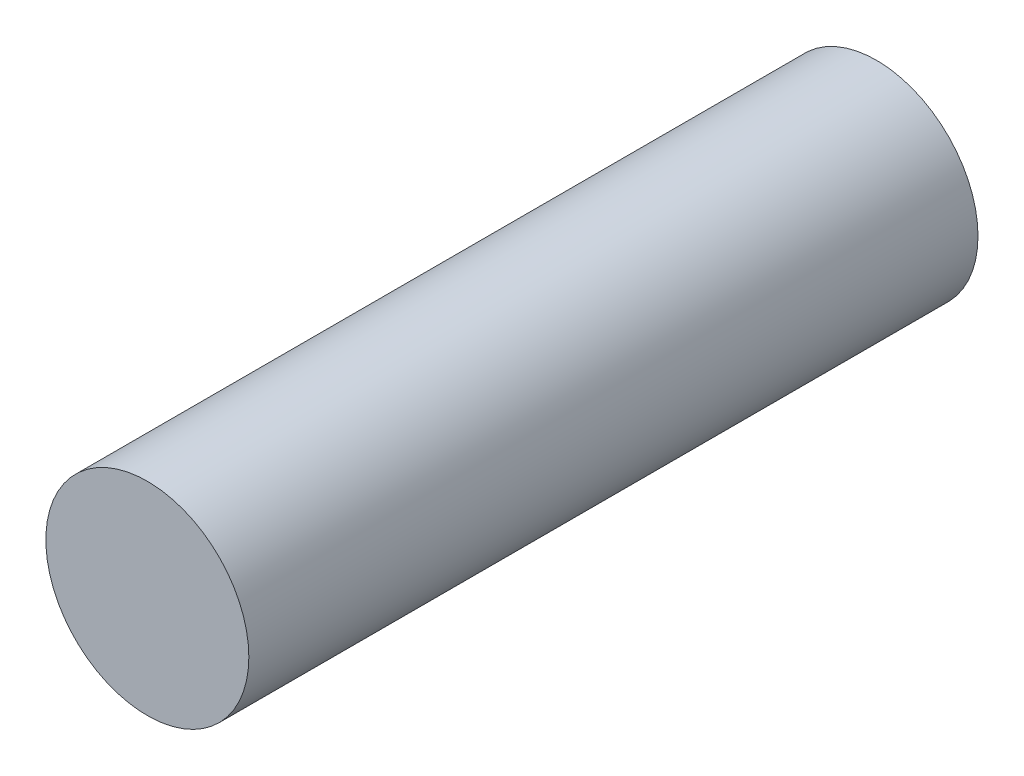
SolidWorks part; units mm, degrees
ref_plane "Front Plane" through (0, 0, 0) normal (0, 0, 1) x (1, 0, 0)
ref_plane "Top Plane" through (0, 0, 0) normal (0, 1, 0) x (1, 0, 0)
ref_plane "Right Plane" through (0, 0, 0) normal (1, 0, 0) x (0, 0, -1)
sketch "Sketch1" plane through (0, 0, 0) normal (0, 0, 1) x (1, 0, 0)
  circle A0 centre (0, 0) radius 24.5
  dimension "D1" = 49
extrude "Boss-Extrude1" add sketch "Sketch1" along normal blind 176
